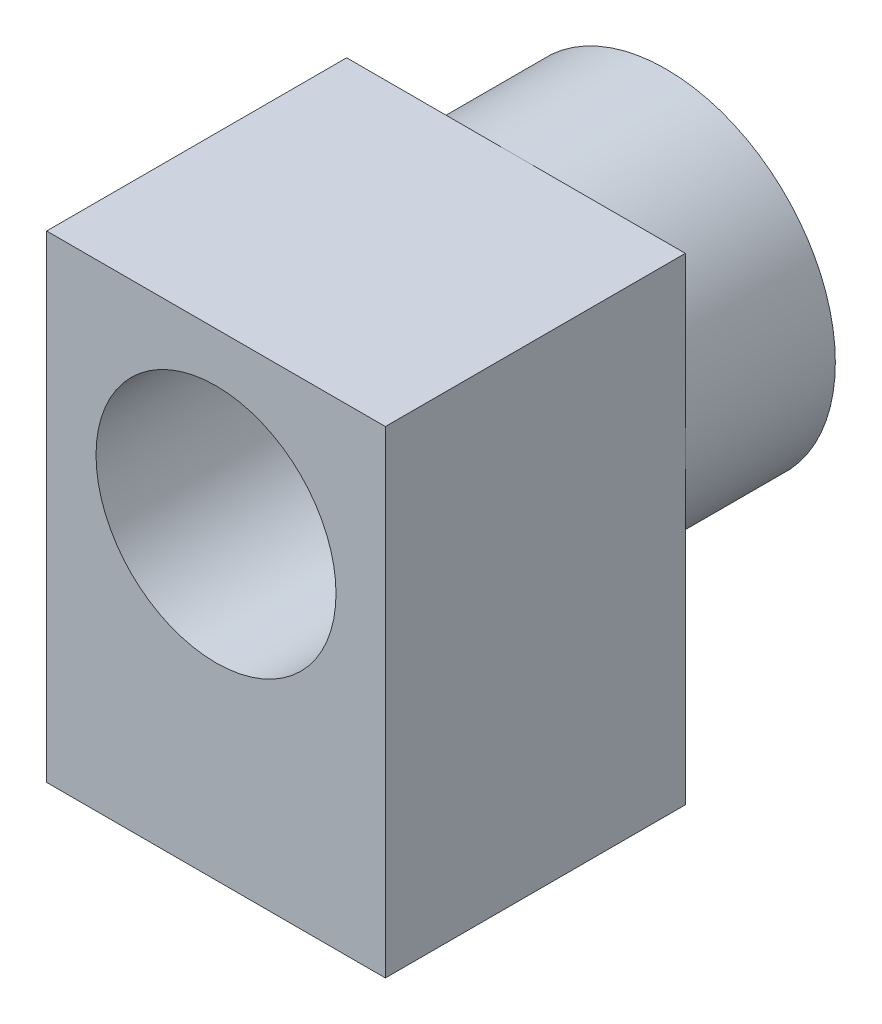
SolidWorks part; units mm, degrees
ref_plane "Front Plane" through (0, 0, 0) normal (0, 0, 1) x (1, 0, 0)
ref_plane "Top Plane" through (0, 0, 0) normal (0, 1, 0) x (1, 0, 0)
ref_plane "Right Plane" through (0, 0, 0) normal (1, 0, 0) x (0, 0, -1)
sketch "Sketch1" plane through (0, 0, 0) normal (0, 0, 1) x (1, 0, 0)
  circle A0 centre (0, 0) radius 8
  circle A1 centre (0, 0) radius 11.2917
  dimension "D1" = 16
  dimension "D2" = 22.5835
extrude "Boss-Extrude1" add sketch "Sketch1" along normal blind 10
sketch "Sketch2" plane through (0, 0, 10) normal (0, 0, 1) x (1, 0, 0)
  line L1 (-11.2917, 11.2917) -> (11.2917, 11.2917)
  line L2 (-11.2917, 11.2917) -> (-11.2917, -20.5484)
  line L3 (-11.2917, -20.5484) -> (11.2917, -20.5484)
  line L4 (11.2917, 11.2917) -> (11.2917, -20.5484)
  circle A0 centre (0, 0) radius 11.2917 construction
  point P0 (0, 0)
  dimension "D1" = 22.5835
extrude "Boss-Extrude2" add sketch "Sketch2" along normal blind 20
sketch "Sketch3" plane through (0, 0, 30) normal (0, 0, 1) x (1, 0, 0)
  circle A0 centre (0, 0) radius 8
  dimension "D1" = 16
extrude "Cut-Extrude1" cut sketch "Sketch3" against normal up to next
